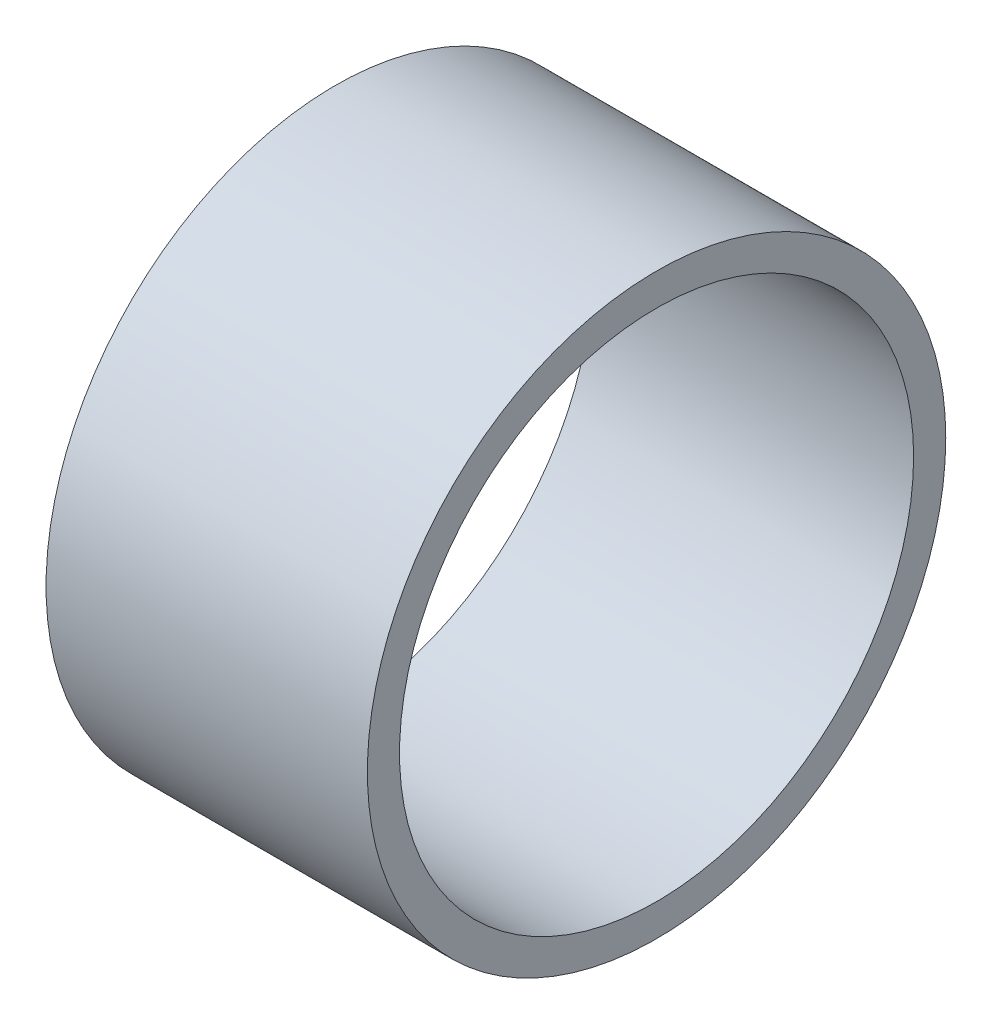
SolidWorks part; units mm, degrees
material "PVC hart"
ref_plane "Ebene vorne" through (0, 0, 0) normal (0, 0, 1) x (1, 0, 0)
ref_plane "Ebene oben" through (0, 0, 0) normal (0, 1, 0) x (1, 0, 0)
ref_plane "Ebene rechts" through (0, 0, 0) normal (1, 0, 0) x (0, 0, -1)
sketch "Skizze1" plane through (0, 0, 0) normal (1, 0, 0) x (0, 0, -1)
  circle A0 centre (0, 0) radius 9
  circle A1 centre (0, 0) radius 8
  dimension "D1" = 16
  dimension "D2" = 18
extrude "Aufsatz-Linear austragen1" add sketch "Skizze1" along normal blind 10
